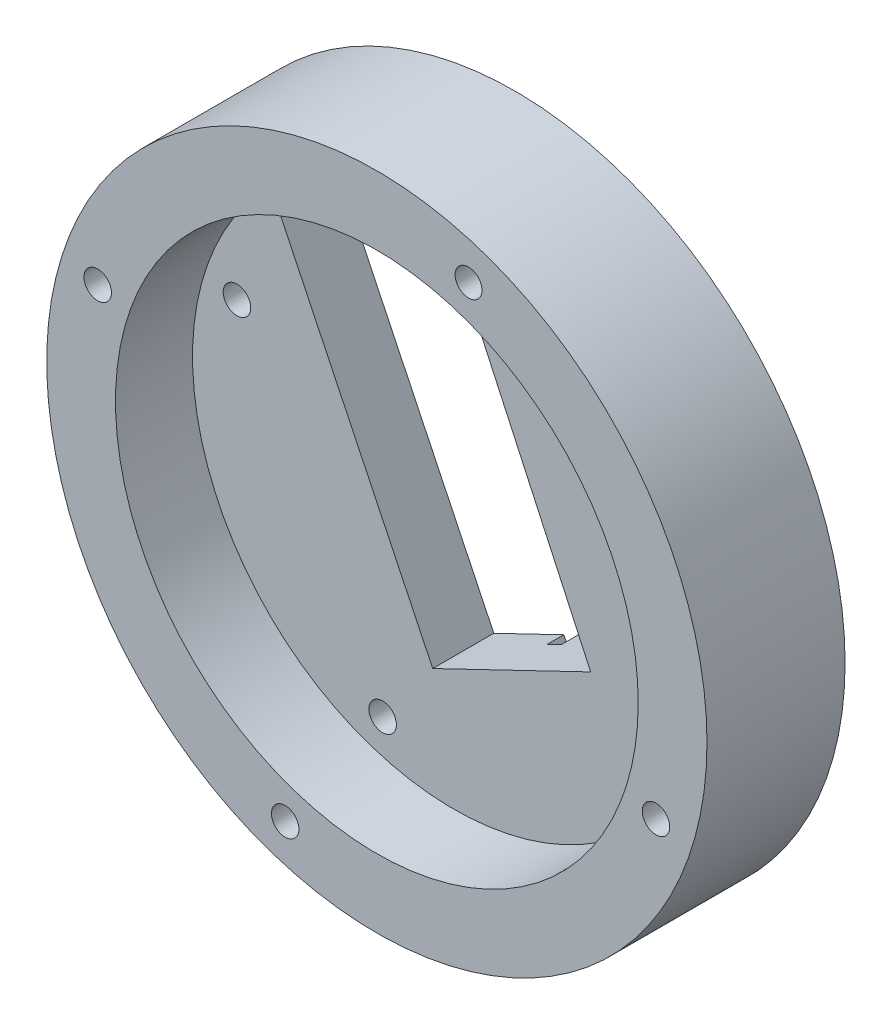
SolidWorks part; units mm, degrees
ref_plane "Front Plane" through (0, 0, 0) normal (0, 0, 1) x (1, 0, 0)
ref_plane "Top Plane" through (0, 0, 0) normal (0, 1, 0) x (1, 0, 0)
ref_plane "Right Plane" through (0, 0, 0) normal (1, 0, 0) x (0, 0, -1)
sketch "Sketch1" plane through (0, 0, 0) normal (0, 0, 1) x (1, 0, 0)
  circle A0 centre (0, 0) radius 60
  dimension "D1" = 120
extrude "Boss-Extrude1" add sketch "Sketch1" along normal blind 25.1
sketch "Sketch2" plane through (0, 0, 25.1) normal (0, 0, 1) x (1, 0, 0)
  circle A0 centre (-16.6647, -50.7331) radius 2.495
  circle A1 centre (-50.7331, 16.6647) radius 2.5
  circle A2 centre (16.6647, 50.7331) radius 2.4444
  circle A3 centre (50.7331, -16.6647) radius 2.5
sketch "Sketch3" plane through (0, 0, 25.1) normal (0, 0, 1) x (1, 0, 0)
  circle A0 centre (0, 0) radius 47.5
  dimension "D1" = 95
extrude "Cut-Extrude2" cut sketch "Sketch3" against normal blind 14
extrude "Cut-Extrude5" cut sketch "Sketch2" against normal through all both and the other way through all
sketch "Sketch6" plane through (0, 0, 0) normal (0, 0, -1) x (-1, 0, 0)
  circle A0 centre (11.9735, 47.2126) radius 3
  circle A1 centre (27.3813, 40.0293) radius 3
  circle A2 centre (-19.7177, -20.7629) radius 3
  circle A3 centre (-4.3099, -27.9462) radius 3
  dimension "D1" = 6
  dimension "D2" = 6
  dimension "D3" = 6
  dimension "D4" = 6
extrude "Cut-Extrude6" cut sketch "Sketch6" against normal blind 6
sketch "Sketch7" plane through (0, 0, 11.1) normal (0, 0, 1) x (1, 0, 0)
  line L0 (-32.7224, 32.7144) -> (-3.8455, -27.2733)
  line L1 (-3.8455, -27.2733) -> (24.8593, -13.4553)
  line L2 (24.8593, -13.4553) -> (-3.0425, 47.0016)
  line L3 (-3.0425, 47.0016) -> (-32.7224, 32.7144)
  circle A0 centre (0, 0) radius 47.1 construction
extrude "Cut-Extrude7" cut sketch "Sketch7" against normal through all both and the other way through all
sketch "Sketch8" plane through (0, 0, 0) normal (0, 0, -1) x (-1, 0, 0)
  circle A0 centre (-39.4274, -12.951) radius 2.5
  circle A1 centre (-12.951, 39.4274) radius 2.5
  circle A2 centre (39.4274, 12.951) radius 2.5
  circle A3 centre (12.951, -39.4274) radius 2.5
  point P20 (0, 0)
  dimension "D1" = 5
  dimension "D2" = 41.5
  dimension "D3" = 4
extrude "Cut-Extrude8" cut sketch "Sketch8" against normal blind 81
sketch "Sketch9" plane through (0, 0, 0) normal (0, 0, -1) x (-1, 0, 0)
  line L0 (-8.8804, -21.1473) -> (-11.8841, -27.3871)
  line L1 (3.8455, -27.2733) -> (-24.8593, -13.4553) construction
  line L2 (-11.8841, -27.3871) -> (-14.4408, -26.1564)
  line L3 (-14.4408, -26.1564) -> (-11.4371, -19.9165)
  line L4 (-11.4371, -19.9165) -> (-8.8804, -21.1473)
  line L5 (19.2843, 39.1832) -> (22.3544, 45.5607)
  line L6 (3.0425, 47.0016) -> (32.7224, 32.7144) construction
  line L7 (22.3544, 45.5607) -> (19.6572, 46.8591)
  line L8 (19.6572, 46.8591) -> (16.5872, 40.4815)
  line L9 (16.5872, 40.4815) -> (19.2843, 39.1832)
extrude "Cut-Extrude9" cut sketch "Sketch9" against normal blind 3
